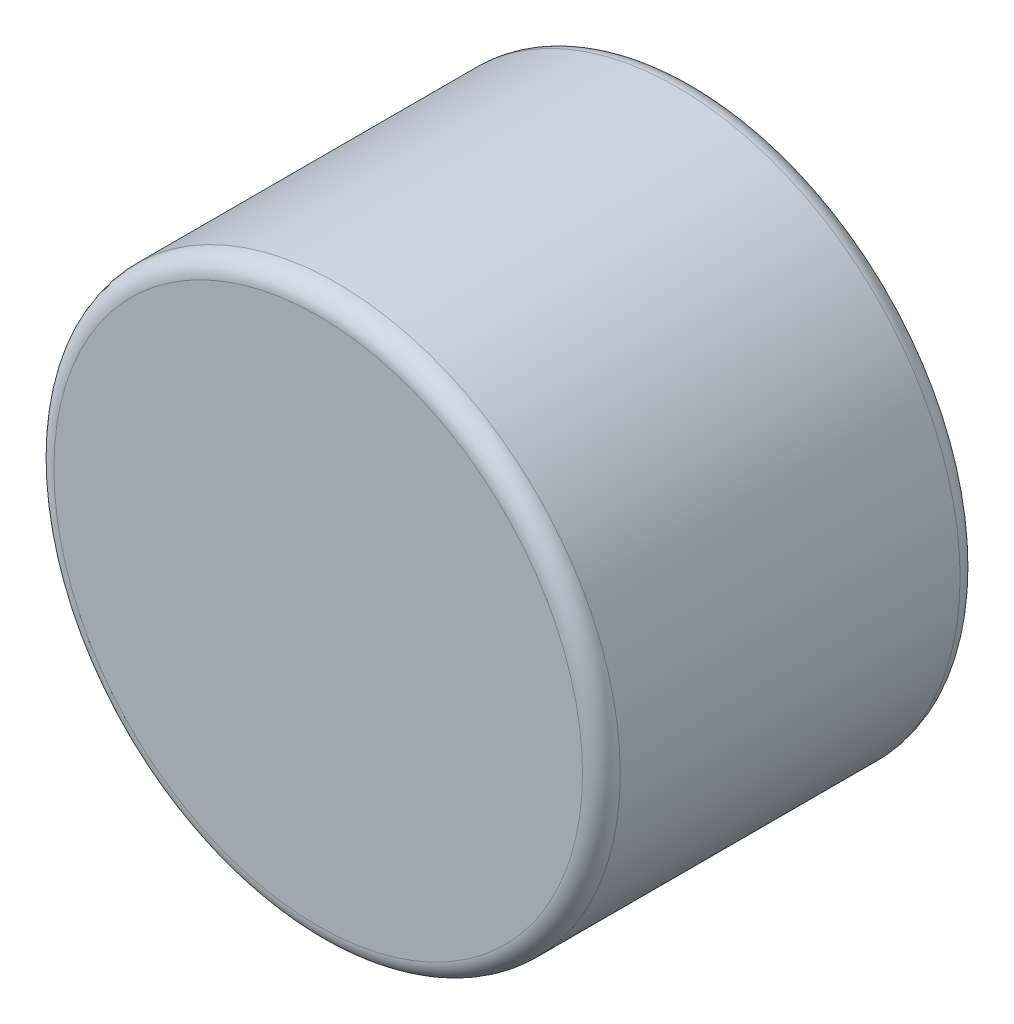
SolidWorks part; units mm, degrees
ref_plane "Front Plane" through (0, 0, 0) normal (0, 0, 1) x (1, 0, 0)
ref_plane "Top Plane" through (0, 0, 0) normal (0, 1, 0) x (1, 0, 0)
ref_plane "Right Plane" through (0, 0, 0) normal (1, 0, 0) x (0, 0, -1)
sketch "Sketch1" plane through (0, 0, 0) normal (0, 0, 1) x (1, 0, 0)
  circle A0 centre (0, 0) radius 38.1
  dimension "D1" = 76.2
extrude "Boss-Extrude1" add sketch "Sketch1" along normal blind 50.8
fillet "Fillet1" radius 2.54 2 edges at (38.1, 0, 0) (38.1, 0, 50.8)
